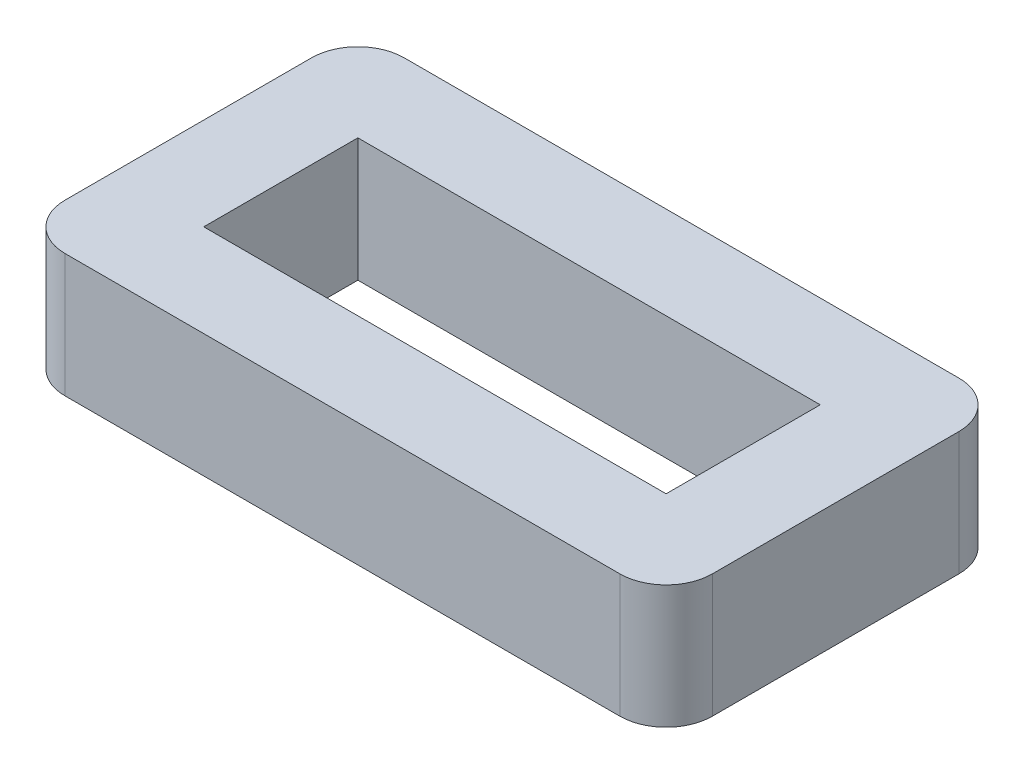
SolidWorks part; units mm, degrees
ref_plane "Alzado" through (0, 0, 0) normal (0, 0, 1) x (1, 0, 0)
ref_plane "Planta" through (0, 0, 0) normal (0, 1, 0) x (1, 0, 0)
ref_plane "Vista lateral" through (0, 0, 0) normal (1, 0, 0) x (0, 0, -1)
sketch "Croquis1" plane through (0, 0, 0) normal (0, 1, 0) x (1, 0, 0)
  line L0 (-10.5, 4) -> (-10.5, -4)
  line L1 (-7.5, 2.5) -> (7.5, 2.5)
  line L2 (-7.5, 2.5) -> (-7.5, -2.5)
  line L3 (-7.5, -2.5) -> (7.5, -2.5)
  line L4 (7.5, 2.5) -> (7.5, -2.5)
  line L5 (-9, -5.5) -> (9, -5.5)
  line L6 (10.5, 4) -> (10.5, -4)
  line L7 (-9, 5.5) -> (9, 5.5)
  line L8 (-10.5, -5.5) -> (10.5, -5.5) construction
  line L9 (10.5, 5.5) -> (10.5, -5.5) construction
  line L10 (-10.5, 5.5) -> (10.5, 5.5) construction
  line L11 (-10.5, 5.5) -> (-10.5, -5.5) construction
  arc A0 (9, -5.5) -> (10.5, -4) centre (9, -4) ccw
  arc A1 (10.5, 4) -> (9, 5.5) centre (9, 4) ccw
  arc A2 (-10.5, -4) -> (-9, -5.5) centre (-9, -4) ccw
  arc A3 (-10.5, 4) -> (-9, 5.5) centre (-9, 4) cw
  point P4 (0, -2.5)
  point P6 (7.5, 0)
  dimension "D4" = 1.5
  dimension "D1" = 5
  dimension "D2" = 15
  dimension "D3" = 3
extrude "Saliente-Extruir1" add sketch "Croquis1" along normal blind 4
